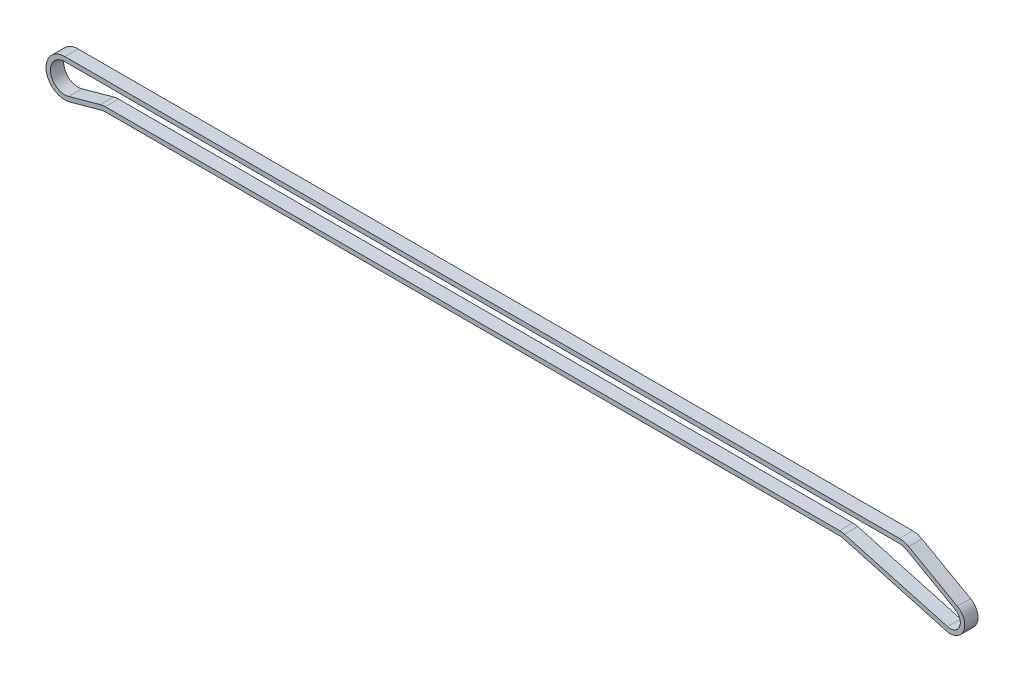
SolidWorks part; units mm, degrees
ref_plane "Front Plane" through (0, 0, 0) normal (0, 0, 1) x (1, 0, 0)
ref_plane "Top Plane" through (0, 0, 0) normal (0, 1, 0) x (1, 0, 0)
ref_plane "Right Plane" through (0, 0, 0) normal (1, 0, 0) x (0, 0, -1)
ref_plane "Plane1" through (0, 0, 6) normal (0, 0, 1) x (1, 0, 0)
sketch "Sketch1" plane through (0, 0, 6) normal (0, 0, 1) x (1, 0, 0)
  line L0 (-28.1811, -10.693) -> (-13.8555, -6.7348)
  line L1 (-12.1244, -6.5) -> (320, -6.5)
  line L2 (321.7315, -6.7349) -> (368.3271, -19.6127)
  line L3 (373.3271, -7.5022) -> (351.3257, 4.904)
  line L4 (347.1507, 6) -> (-30.4449, 6)
  line L5 (350.3433, 3.1619) -> (372.3447, -9.2443)
  line L6 (368.8599, -17.6849) -> (322.2643, -4.8071)
  line L7 (320, -4.5) -> (-12.1244, -4.5)
  line L8 (-14.3881, -4.807) -> (-28.7137, -8.7652)
  line L9 (-30.4449, 4) -> (347.1507, 4)
  arc A0 (-30.4449, 6) -> (-28.1811, -10.693) centre (-30.4449, -2.5) ccw
  arc A1 (-13.8555, -6.7348) -> (-12.1244, -6.5) centre (-12.1244, -13) cw
  arc A2 (320, -6.5) -> (321.7315, -6.7349) centre (320, -13) cw
  arc A3 (368.3271, -19.6127) -> (373.3271, -7.5022) centre (370.0853, -13.2512) ccw
  arc A4 (351.3257, 4.904) -> (347.1507, 6) centre (347.1507, -2.5) ccw
  arc A5 (372.3447, -9.2443) -> (368.8599, -17.6849) centre (370.0853, -13.2512) cw
  arc A6 (322.2643, -4.8071) -> (320, -4.5) centre (320, -13) ccw
  arc A7 (-12.1244, -4.5) -> (-14.3881, -4.807) centre (-12.1244, -13) ccw
  arc A8 (-28.7137, -8.7652) -> (-30.4449, 4) centre (-30.4449, -2.5) cw
  arc A9 (347.1507, 4) -> (350.3433, 3.1619) centre (347.1507, -2.5) cw
extrude "Boss-Extrude1" add sketch "Sketch1" against normal blind 6
